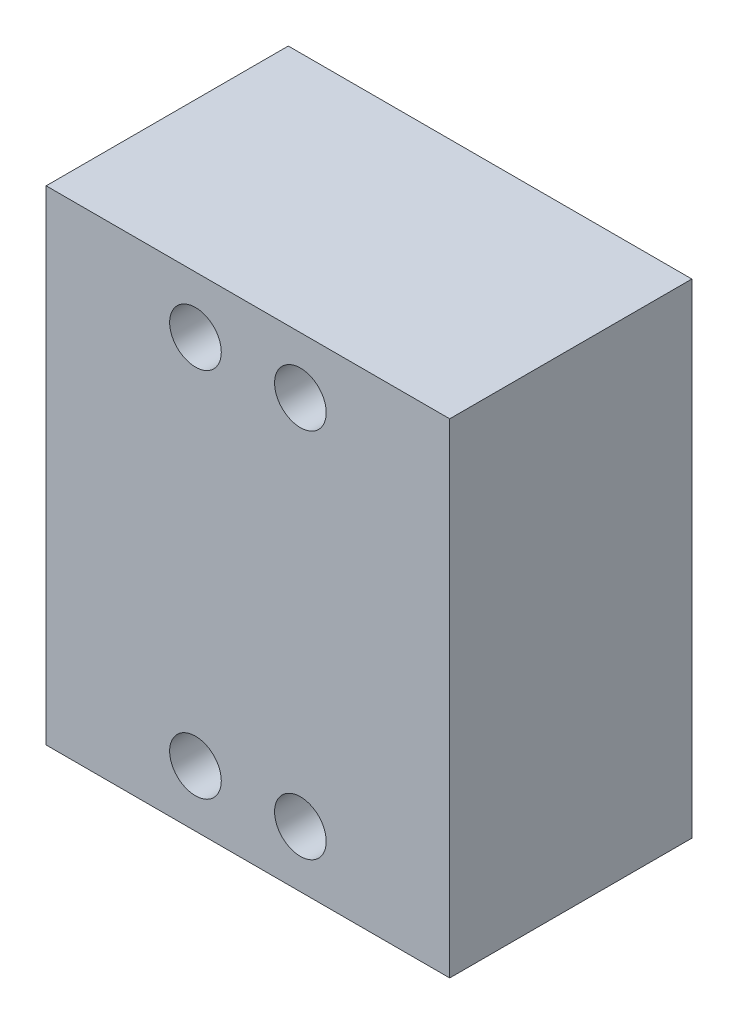
SolidWorks part; units mm, degrees
ref_plane "Front Plane" through (0, 0, 0) normal (0, 0, 1) x (1, 0, 0)
ref_plane "Top Plane" through (0, 0, 0) normal (0, 1, 0) x (1, 0, 0)
ref_plane "Right Plane" through (0, 0, 0) normal (1, 0, 0) x (0, 0, -1)
sketch "Sketch1" plane through (0, 0, 0) normal (0, 0, 1) x (1, 0, 0)
  line L0 (55, 0) -> (-55, 0) construction
  line L1 (-25, 30) -> (25, 30)
  line L2 (-25, 30) -> (-25, -30)
  line L3 (-25, -30) -> (25, -30)
  line L4 (25, 30) -> (25, -30)
  line L5 (0, -55) -> (0, 55) construction
  dimension "D1" = 50
  dimension "D2" = 60
  dimension "D3" = 30
  dimension "D4" = 25
extrude "Boss-Extrude1" add sketch "Sketch1" along normal blind 30
hole_wizard "M6 Clearance Hole1" positions "Sketch5" profile "Sketch4" hole size "M6" standard "ISO" end condition through all
sketch "Sketch5" plane through (0, 0, 30) normal (0, 0, 1) x (1, 0, 0)
  line L1 (55, 0) -> (-55, 0) construction
  line L2 (-63.4314, 0) -> (43.331, 0) construction
  line L3 (0, -55) -> (0, 55) construction
  line L4 (0, 43.8481) -> (0, -35.5104) construction
  point P0 (-6.5, 23)
  point P16 (-6.5, -23)
  point P26 (6.5, -23)
  point P27 (6.5, 23)
  dimension "D1" = 6.5
  dimension "D3" = 23
sketch "Sketch4" plane through (-6.5, 23, 30) normal (1, 0, 0) x (0, -1, 0)
  line L0 (0, 0) -> (0, 30)
  line L1 (0, 30) -> (3.2, 30)
  line L2 (3.2, 30) -> (3.2, 0)
  line L5 (3.2, 0) -> (0, 0)
  line L11 (0, -6.35) -> (0, 107.95) construction
  dimension "Thru Hole Dia." = 6.4
  dimension "Thru Hole Depth" = 30
